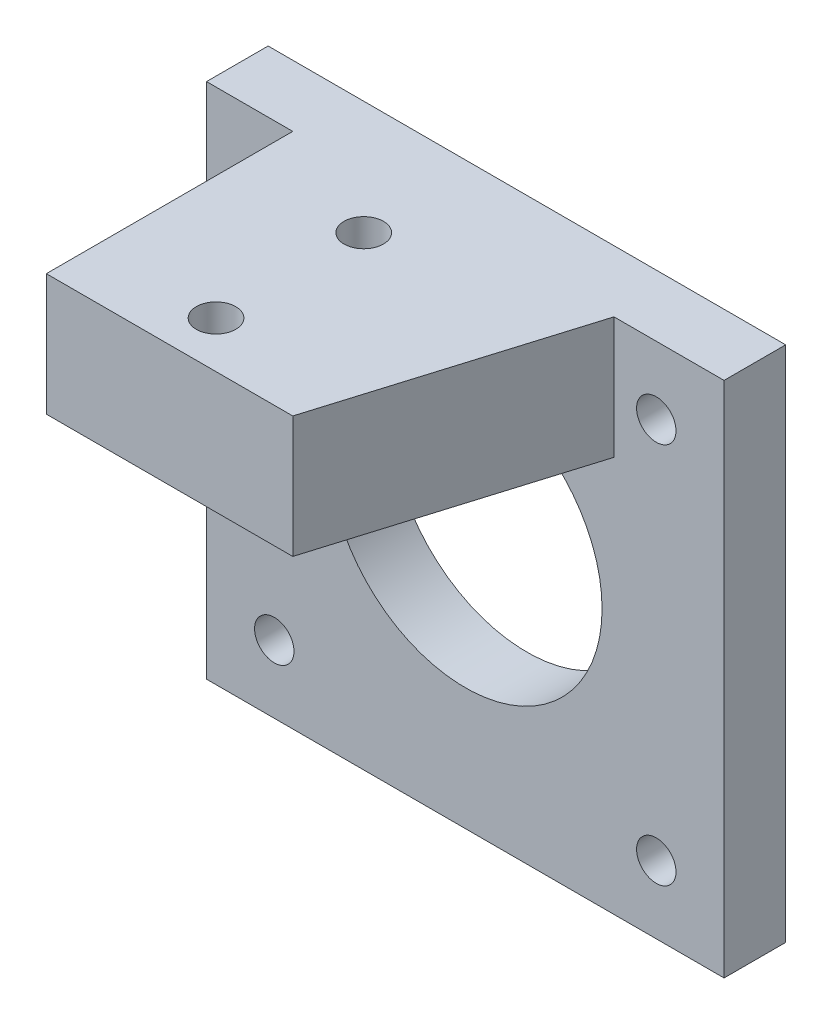
SolidWorks part; units mm, degrees
ref_plane "前视基准面" through (0, 0, 0) normal (0, 0, 1) x (1, 0, 0)
ref_plane "上视基准面" through (0, 0, 0) normal (0, 1, 0) x (1, 0, 0)
ref_plane "右视基准面" through (0, 0, 0) normal (1, 0, 0) x (0, 0, -1)
sketch "草图1" plane through (0, 0, 0) normal (0, 0, 1) x (1, 0, 0)
  line L0 (21, 42) -> (21, -49958) construction
  line L1 (0, 0) -> (42, 0)
  line L2 (0, 0) -> (0, 42)
  line L3 (0, 42) -> (42, 42)
  line L4 (42, 0) -> (42, 42)
  line L5 (0, 21) -> (50000, 21) construction
  circle A0 centre (21, 21) radius 11.1
  point P7 (21, 42)
  point P8 (21, 0)
  point P11 (0, 21)
  point P12 (42, 21)
  dimension "D3" = 22.2
  dimension "D1" = 42
  dimension "D2" = 42
extrude "凸台-拉伸1" add sketch "草图1" along normal blind 5
sketch "草图2" plane through (0, 0, 5) normal (0, 0, 1) x (1, 0, 0)
  line L0 (21, 42) -> (21, 21) construction
  line L1 (42, 42) -> (0, 42) construction
  line L2 (21, 21) -> (43.574, 21) construction
  circle A0 centre (36.5, 36.5) radius 1.6
  circle A1 centre (5.5, 36.5) radius 1.6
  circle A2 centre (36.5, 5.5) radius 1.6
  circle A3 centre (5.5, 5.5) radius 1.6
  dimension "D1" = 3.2
  dimension "D2" = 31
  dimension "D3" = 31
extrude "切除-拉伸1" cut sketch "草图2" against normal through all
sketch "草图4" plane through (0, 0, 5) normal (0, 0, 1) x (1, 0, 0)
  line L0 (21, 42) -> (21, -49958) construction
  line L1 (42, 42) -> (0, 42) construction
  line L2 (0, 0) -> (42, 0) construction
  line L4 (7, 42) -> (27, 42)
  line L5 (7, 42) -> (7, 32.1257)
  line L6 (7, 32.1257) -> (27, 32.1257)
  line L7 (27, 42) -> (27, 32.1257)
  point P4 (21, 42)
  point P7 (21, 0)
  dimension "D1" = 20
  dimension "D2" = 6
extrude "凸台-拉伸2" add sketch "草图4" along normal blind 20
sketch "草图5" plane through (0, 32.1257, 0) normal (0, -1, 0) x (1, 0, 0)
  line L0 (17, 25) -> (17, 8.7019) construction
  line L1 (7, 25) -> (27, 25) construction
  circle A0 centre (17, 21.229) radius 1.6
  circle A1 centre (17, 9.2412) radius 1.6
  dimension "D1" = 3.2
  dimension "D2" = 3.2
extrude "切除-拉伸2" cut sketch "草图5" against normal blind 20
sketch "草图6" plane through (0, 32.1257, 0) normal (0, -1, 0) x (1, 0, 0)
  circle A0 centre (17, 21.229) radius 3
  circle A1 centre (17, 9.2412) radius 3
  dimension "D1" = 6
  dimension "D2" = 6
extrude "切除-拉伸3" cut sketch "草图6" against normal blind 3
sketch "草图7" plane through (0, 32.1257, 0) normal (0, -1, 0) x (1, 0, 0)
  line L0 (27, 5) -> (33.0663, 5)
  line L1 (0, 5) -> (42, 5) construction
  line L2 (33.0663, 5) -> (27, 25)
  line L3 (27, 25) -> (27, 5)
extrude "凸台-拉伸3" add sketch "草图7" against normal up to vertex (9.8743 mm away) up to point (27, 42, 5)
